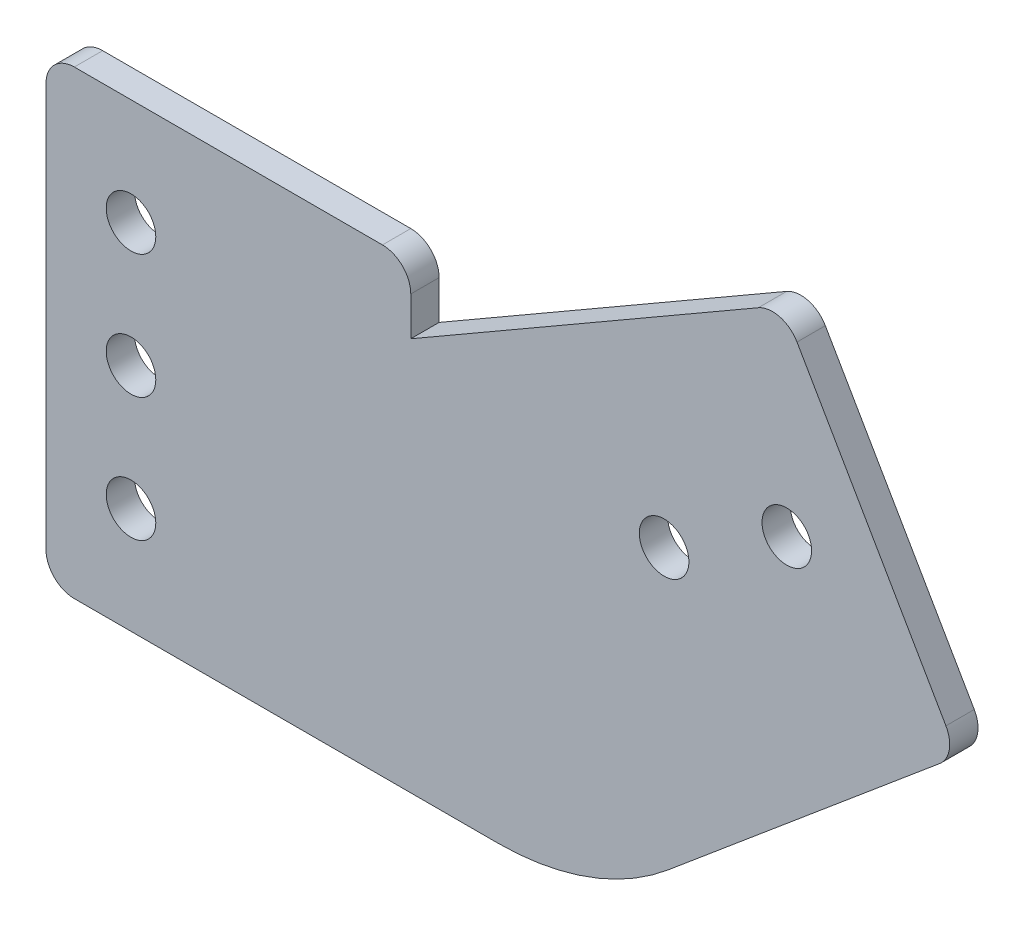
SolidWorks part; units mm, degrees
material "1060 Alloy"
ref_plane "Front Plane" through (0, 0, 0) normal (0, 0, 1) x (1, 0, 0)
ref_plane "Top Plane" through (0, 0, 0) normal (0, 1, 0) x (1, 0, 0)
ref_plane "Right Plane" through (0, 0, 0) normal (1, 0, 0) x (0, 0, -1)
sketch "Sketch1" plane through (0, 0, 0) normal (0, 0, 1) x (1, 0, 0)
  line L0 (26.75, 29.1279) -> (26.75, 33.5) construction
  line L1 (26.75, 33.5) -> (0, 33.5) construction
  line L2 (0, 33.5) -> (0, 0) construction
  line L3 (0, 0) -> (32.3773, 0) construction
  line L4 (44.7509, 4.5036) -> (65.507, 21.92) construction
  line L5 (65.507, 21.92) -> (52.6966, 44.1082) construction
  line L6 (52.6966, 44.1082) -> (26.75, 29.1279) construction
  line L7 (59.0716, 33.0663) -> (34.0063, 18.5949) construction
  line L8 (6.5, 33.5) -> (6.5, 1.8364) construction
  line L9 (24.25, 33) -> (2.5, 33)
  line L10 (0.5, 31) -> (0.5, 2.5)
  line L11 (2.5, 0.5) -> (32.3773, 0.5)
  line L12 (44.4296, 4.8867) -> (63.5786, 20.9546)
  line L13 (64.0251, 23.4867) -> (53.5136, 41.6931)
  line L14 (50.7816, 42.4252) -> (26.25, 28.2619)
  line L15 (26.25, 28.2619) -> (26.25, 31)
  line L16 (52.5136, 43.4252) -> (26.25, 28.2619) construction
  line L17 (64.8642, 22.0334) -> (52.5136, 43.4252) construction
  line L18 (44.4296, 4.8867) -> (64.8642, 22.0334) construction
  line L19 (0.5, 0.5) -> (32.3773, 0.5) construction
  line L20 (0.5, 33) -> (0.5, 0.5) construction
  line L21 (26.25, 33) -> (0.5, 33) construction
  line L22 (26.25, 28.2619) -> (26.25, 33) construction
  arc A0 (32.3773, 0) -> (44.7509, 4.5036) centre (32.3773, 19.25) ccw construction
  circle A1 centre (52.7929, 29.4413) radius 1.75
  circle A2 centre (44.1327, 24.4413) radius 1.75
  circle A3 centre (6.5, 25.5) radius 1.75
  circle A4 centre (6.5, 16.75) radius 1.75
  circle A5 centre (6.5, 8) radius 1.75
  arc A6 (32.3773, 0.5) -> (44.4296, 4.8867) centre (32.3773, 19.25) ccw
  arc A7 (50.7816, 42.4252) -> (53.5136, 41.6931) centre (51.7816, 40.6931) cw
  arc A8 (64.0251, 23.4867) -> (63.5786, 20.9546) centre (62.293, 22.4867) cw
  arc A9 (2.5, 0.5) -> (0.5, 2.5) centre (2.5, 2.5) cw
  arc A10 (0.5, 31) -> (2.5, 33) centre (2.5, 31) cw
  arc A11 (24.25, 33) -> (26.25, 31) centre (24.25, 31) cw
  point P12 (45.1356, 9.6723)
  point P24 (0, 0)
  point P25 (0, 0)
  point P26 (0, 0)
  point P51 (0, 0)
  dimension "D3" = 19.25
  dimension "D4" = 10
  dimension "D12" = 3.5
  dimension "D18" = 2
  dimension "D1" = 33.5
  dimension "D2" = 32.3773
  dimension "D5" = 26.75
  dimension "D6" = 29.9606
  dimension "D7" = 25.6207
  dimension "D8" = 4.3721
  dimension "D9" = 80
  dimension "D10" = 7.25
  dimension "D11" = 12.75
  dimension "D13" = 6.5
  dimension "D14" = 8
  dimension "D15" = 8.75
  dimension "D16" = 8.75
  dimension "D19" = 24.9973
  dimension "D17" = 0.5
extrude "Boss-Extrude1" add sketch "Sketch1" along normal blind 2
